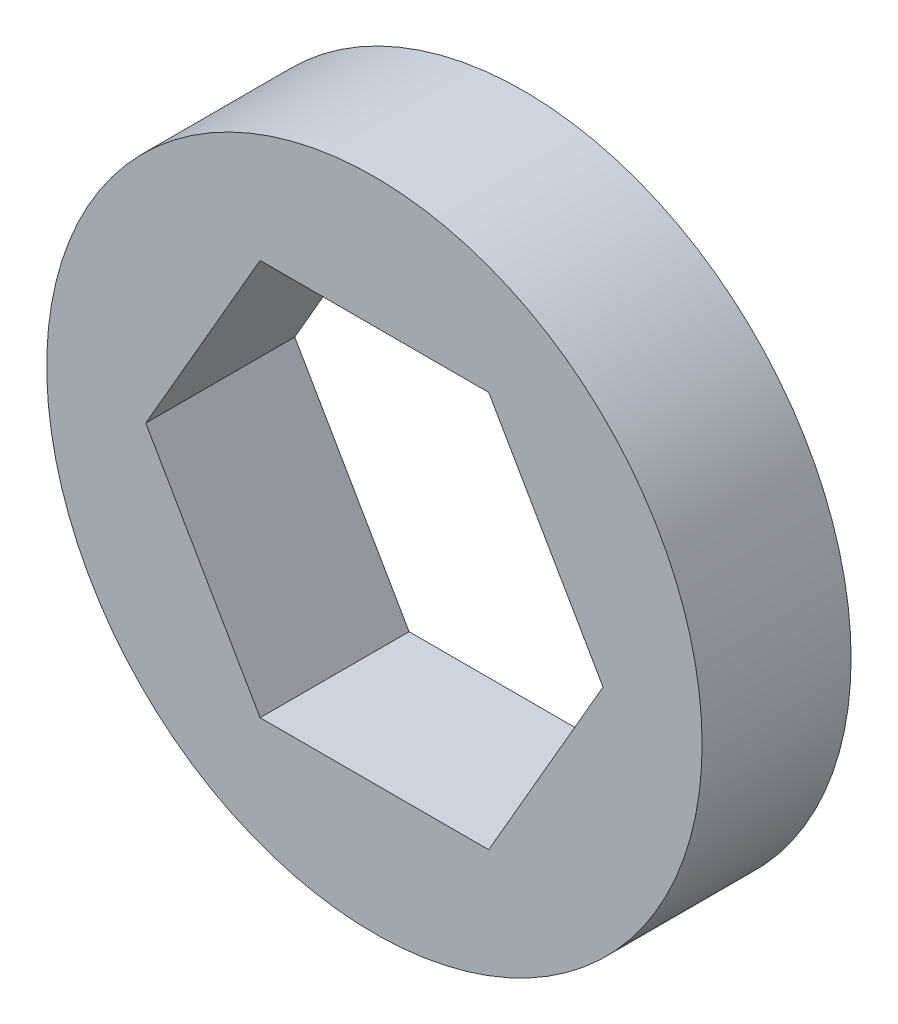
SolidWorks part; units mm, degrees
material "1060 Alloy"
ref_plane "Front Plane" through (0, 0, 0) normal (0, 0, 1) x (1, 0, 0)
ref_plane "Top Plane" through (0, 0, 0) normal (0, 1, 0) x (1, 0, 0)
ref_plane "Right Plane" through (0, 0, 0) normal (1, 0, 0) x (0, 0, -1)
sketch "Sketch1" plane through (0, 0, 0) normal (0, 0, 1) x (1, 0, 0)
  line L1 (-7.3279, 0) -> (-3.6639, -6.3461)
  line L2 (-3.6639, -6.3461) -> (3.664, -6.3461)
  line L3 (3.664, -6.3461) -> (7.3279, 0)
  line L4 (7.3279, 0) -> (3.6639, 6.3461)
  line L5 (3.6639, 6.3461) -> (-3.664, 6.3461)
  line L6 (-3.664, 6.3461) -> (-7.3279, 0)
  circle A0 centre (0, 0) radius 10.5029
  circle A1 centre (0, 0) radius 7.3279 construction
  circle A2 centre (0, 0) radius 6.3461 construction
  dimension "D1" = 14.6558
  dimension "D2" = 21.0058
extrude "Boss-Extrude1" add sketch "Sketch1" along normal blind 4.7752
